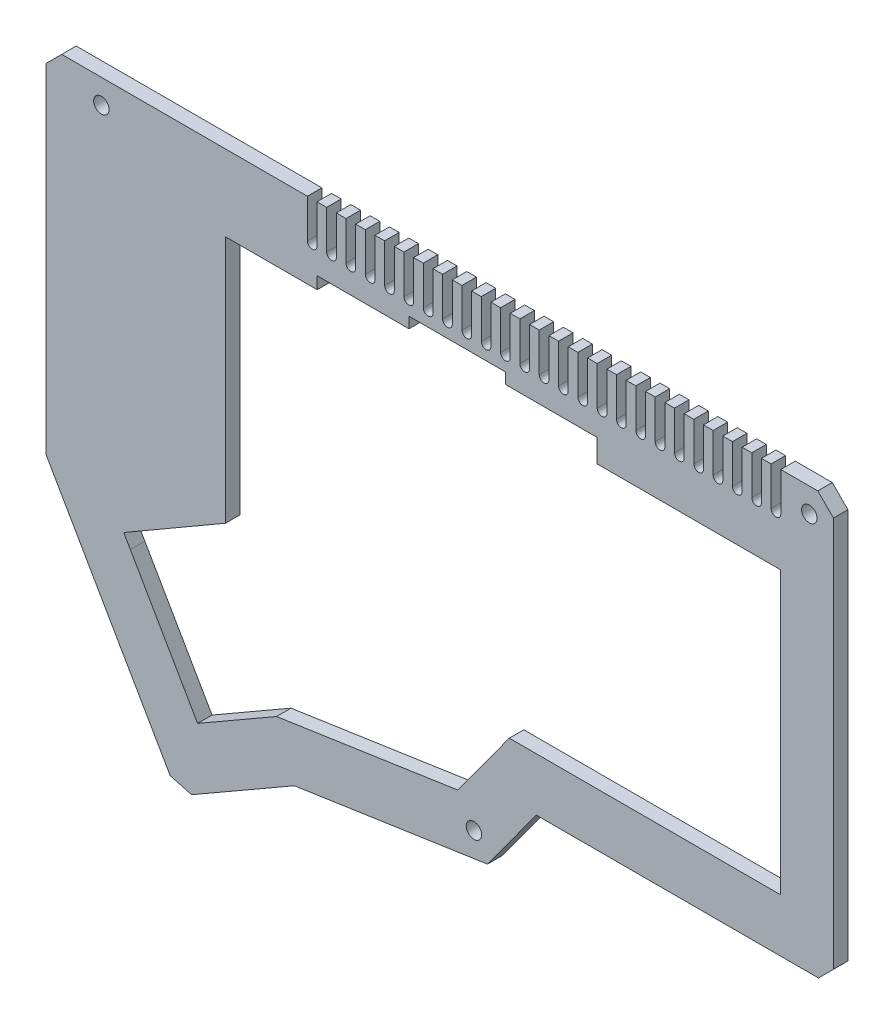
SolidWorks part; units mm, degrees
ref_plane "Plan de face" through (0, 0, 0) normal (0, 0, 1) x (1, 0, 0)
ref_plane "Plan de dessus" through (0, 0, 0) normal (0, 1, 0) x (1, 0, 0)
ref_plane "Plan de droite" through (0, 0, 0) normal (1, 0, 0) x (0, 0, -1)
sketch "Esquisse1" plane through (0, 0, 0) normal (0, 0, 1) x (1, 0, 0)
  line L0 (-117.3419, -15.4198) -> (-103.3409, -15.4198) construction
  line L1 (-103.3409, -15.4198) -> (-103.3409, -29.4208) construction
  line L2 (-103.3409, -29.4208) -> (-117.3419, -29.4208) construction
  line L3 (-117.3419, -29.4208) -> (-117.3419, -15.4198) construction
  line L4 (-98.3406, -27.0457) -> (-98.3406, -13.0447) construction
  line L5 (-98.3406, -13.0447) -> (-84.3396, -13.0447) construction
  line L6 (-84.3396, -13.0447) -> (-84.3396, -27.0457) construction
  line L7 (-84.3396, -27.0457) -> (-98.3406, -27.0457) construction
  line L8 (-79.3392, -24.6705) -> (-79.3392, -10.6695) construction
  line L9 (-79.3392, -10.6695) -> (-65.3382, -10.6695) construction
  line L10 (-65.3382, -10.6695) -> (-65.3382, -24.6705) construction
  line L11 (-65.3382, -24.6705) -> (-79.3392, -24.6705) construction
  line L12 (-60.3379, -27.0457) -> (-60.3379, -13.0447) construction
  line L13 (-60.3379, -13.0447) -> (-46.3369, -13.0447) construction
  line L14 (-46.3369, -13.0447) -> (-46.3369, -27.0457) construction
  line L15 (-46.3369, -27.0457) -> (-60.3379, -27.0457) construction
  line L16 (-41.3365, -31.796) -> (-41.3365, -17.795) construction
  line L17 (-41.3365, -17.795) -> (-27.3355, -17.795) construction
  line L18 (-27.3355, -17.795) -> (-27.3355, -31.796) construction
  line L19 (-27.3355, -31.796) -> (-41.3365, -31.796) construction
  line L20 (-22.3347, -31.796) -> (-22.3347, -17.795) construction
  line L21 (-22.3347, -17.795) -> (-8.3337, -17.795) construction
  line L22 (-8.3337, -17.795) -> (-8.3337, -31.796) construction
  line L23 (-8.3337, -31.796) -> (-22.3347, -31.796) construction
  line L24 (-117.3419, -34.4212) -> (-103.3409, -34.4212) construction
  line L25 (-103.3409, -34.4212) -> (-103.3409, -48.4222) construction
  line L26 (-103.3409, -48.4222) -> (-117.3419, -48.4222) construction
  line L27 (-117.3419, -48.4222) -> (-117.3419, -34.4212) construction
  line L28 (-98.3406, -32.046) -> (-84.3396, -32.046) construction
  line L29 (-84.3396, -32.046) -> (-84.3396, -46.047) construction
  line L30 (-84.3396, -46.047) -> (-98.3406, -46.047) construction
  line L31 (-98.3406, -46.047) -> (-98.3406, -32.046) construction
  line L32 (-79.3392, -29.6709) -> (-65.3382, -29.6709) construction
  line L33 (-65.3382, -29.6709) -> (-65.3382, -43.6718) construction
  line L34 (-65.3382, -43.6718) -> (-79.3392, -43.6718) construction
  line L35 (-79.3392, -43.6718) -> (-79.3392, -29.6709) construction
  line L36 (-60.3379, -32.046) -> (-46.3369, -32.046) construction
  line L37 (-46.3369, -32.046) -> (-46.3369, -46.047) construction
  line L38 (-46.3369, -46.047) -> (-60.3379, -46.047) construction
  line L39 (-60.3379, -46.047) -> (-60.3379, -32.046) construction
  line L40 (-41.3365, -36.7964) -> (-27.3355, -36.7964) construction
  line L41 (-27.3355, -36.7964) -> (-27.3355, -50.7973) construction
  line L42 (-27.3355, -50.7973) -> (-41.3365, -50.7973) construction
  line L43 (-41.3365, -50.7973) -> (-41.3365, -36.7964) construction
  line L44 (-22.3347, -36.7964) -> (-8.3337, -36.7964) construction
  line L45 (-8.3337, -36.7964) -> (-8.3337, -50.7973) construction
  line L46 (-8.3337, -50.7973) -> (-22.3347, -50.7973) construction
  line L47 (-22.3347, -50.7973) -> (-22.3347, -36.7964) construction
  line L48 (-22.3347, -55.7977) -> (-8.3337, -55.7977) construction
  line L49 (-8.3337, -55.7977) -> (-8.3337, -69.7987) construction
  line L50 (-8.3337, -69.7987) -> (-22.3347, -69.7987) construction
  line L51 (-22.3347, -69.7987) -> (-22.3347, -55.7977) construction
  line L52 (-41.3365, -55.7977) -> (-27.3355, -55.7977) construction
  line L53 (-27.3355, -55.7977) -> (-27.3355, -69.7987) construction
  line L54 (-27.3355, -69.7987) -> (-41.3365, -69.7987) construction
  line L55 (-41.3365, -69.7987) -> (-41.3365, -55.7977) construction
  line L56 (-60.3379, -51.0474) -> (-46.3369, -51.0474) construction
  line L57 (-46.3369, -51.0474) -> (-46.3369, -65.0484) construction
  line L58 (-46.3369, -65.0484) -> (-60.3379, -65.0484) construction
  line L59 (-60.3379, -65.0484) -> (-60.3379, -51.0474) construction
  line L60 (-79.3392, -48.6722) -> (-65.3382, -48.6722) construction
  line L61 (-65.3382, -48.6722) -> (-65.3382, -62.6732) construction
  line L62 (-65.3382, -62.6732) -> (-79.3392, -62.6732) construction
  line L63 (-79.3392, -62.6732) -> (-79.3392, -48.6722) construction
  line L64 (-98.3406, -51.0474) -> (-84.3396, -51.0474) construction
  line L65 (-84.3396, -51.0474) -> (-84.3396, -65.0484) construction
  line L66 (-84.3396, -65.0484) -> (-98.3406, -65.0484) construction
  line L67 (-98.3406, -65.0484) -> (-98.3406, -51.0474) construction
  line L68 (-117.3419, -53.4225) -> (-103.3409, -53.4225) construction
  line L69 (-103.3409, -53.4225) -> (-103.3409, -67.4235) construction
  line L70 (-103.3409, -67.4235) -> (-117.3419, -67.4235) construction
  line L71 (-117.3419, -67.4235) -> (-117.3419, -53.4225) construction
  line L72 (-88.8399, -70.6738) -> (-74.8389, -70.6738) construction
  line L73 (-74.8389, -70.6738) -> (-74.8389, -84.6747) construction
  line L74 (-74.8389, -84.6747) -> (-88.8399, -84.6747) construction
  line L75 (-88.8399, -84.6747) -> (-88.8399, -70.6738) construction
  line L76 (-111.4175, -75.4665) -> (-97.8899, -71.8565) construction
  line L77 (-97.8899, -71.8565) -> (-94.28, -85.3841) construction
  line L78 (-94.28, -85.3841) -> (-107.8075, -88.9941) construction
  line L79 (-107.8075, -88.9941) -> (-111.4175, -75.4665) construction
  line L80 (-134.6581, -81.5997) -> (-122.5281, -74.6075) construction
  line L81 (-122.5281, -74.6075) -> (-115.5359, -86.7375) construction
  line L82 (-115.5359, -86.7375) -> (-127.6659, -93.7297) construction
  line L83 (-127.6659, -93.7297) -> (-134.6581, -81.5997) construction
  line L86 (-6.475, -71.9336) -> (-62.0853, -71.9336) construction
  line L89 (-72.824, -86.6446) -> (-62.0853, -71.9336) construction
  line L96 (-109.7697, -91.4639) -> (-73.0906, -86.6918) construction
  line L97 (-124.664, -99.8297) -> (-110.3971, -91.5881) construction
  line L98 (-139.9408, -76.5013) -> (-126.7151, -99.4281) construction
  line L99 (-119.8527, -15.5421) -> (-139.6028, -15.5421) construction
  line L100 (-100.8528, -13.2921) -> (-118.8527, -13.2921) construction
  line L101 (-63.8455, -8.5421) -> (-80.8528, -8.5421) construction
  line L102 (-44.8455, -10.792) -> (-62.8485, -10.792) construction
  line L103 (-25.8456, -15.5421) -> (-43.8486, -15.5421) construction
  line L104 (-6.8456, -15.5421) -> (-23.8529, -15.5421) construction
  line L105 (-6.2741, -71.3672) -> (-6.2741, -16.1136) construction
  line L106 (-23.8529, -71.9423) -> (-6.8456, -71.9423) construction
  line L107 (-61.8455, -71.9423) -> (-25.8456, -71.9423) construction
  line L108 (-72.6738, -86.4911) -> (-62.1363, -72.0583) construction
  line L109 (-140.1743, -16.1136) -> (-140.1743, -75.5958) construction
  line L110 (-134.3462, 1.5705) -> (-134.3466, -55.7217) construction
  line L111 (-134.3466, -55.7217) -> (-160.479, -70.8411) construction
  line L112 (-160.479, -70.8411) -> (-133.7613, -117.344) construction
  line L113 (-126.937, -119.1852) -> (-105.0783, -106.604) construction
  line L114 (-105.0783, -106.604) -> (-64.4097, -100.5586) construction
  line L115 (-64.4097, -100.5586) -> (-54.4636, -86.9336) construction
  line L116 (3.6609, -86.9336) -> (-54.4636, -86.9336) construction
  line L117 (8.525, -82.0695) -> (8.525, 1.315) construction
  line L122 (3.525, 6.3153) -> (-96.3444, 6.3209) construction
  line L129 (8.525, -86.9336) -> (8.525, -0.6796) construction
  line L130 (-48.3431, 6.3182) -> (-96.3444, 6.3209) construction
  line L131 (-115.3458, 1.5705) -> (-134.3462, 1.5705) construction
  line L132 (-160.479, -3.4295) -> (-160.479, -70.8411) construction
  line L135 (-119.3466, -64.3728) -> (-135.695, -73.8315) construction
  line L136 (-140.0228, -76.3355) -> (-140.0228, -76.3321)
  line L138 (-160.479, -70.8411) -> (-131.2704, -121.6794) construction
  line L139 (-131.2704, -121.6794) -> (-105.0783, -106.604) construction
  line L140 (-133.7613, -117.344) -> (-126.937, -119.1852) construction
  line L142 (8.525, 1.315) -> (3.525, 6.3153) construction
  line L143 (8.525, -86.9336) -> (-54.4636, -86.9336) construction
  line L144 (8.525, -82.0695) -> (3.6609, -86.9336) construction
  line L148 (-103.3409, 6.3209) -> (-119.3463, 6.3209) construction
  line L149 (-119.3463, 6.3209) -> (-119.3463, 1.5705) construction
  line L150 (-140.0228, 1.5705) -> (-140.0228, 6.3209) construction
  line L151 (-140.0228, 6.3209) -> (-155.479, 6.3209) construction
  line L152 (-160.479, 1.3209) -> (-160.479, -3.4295) construction
  line L153 (-155.479, 6.3209) -> (-160.479, 1.3209) construction
  line L154 (8.525, -1.685) -> (-119.3463, -1.6779) construction
  line L155 (-146.0924, -79.8227) -> (-128.3223, -110.752) construction
  line L156 (-128.3223, -110.752) -> (-107.7547, -98.9139) construction
  line L157 (-140.0228, -78.3428) -> (-126.1111, -102.5565)
  line L158 (-126.1111, -102.5565) -> (-109.762, -93.1464)
  line L159 (-109.762, -93.1464) -> (-72.2631, -87.5722)
  line L160 (-72.2631, -87.5722) -> (-61.5772, -72.9336)
  line L161 (-5.475, -72.9336) -> (-61.5772, -72.9336)
  line L162 (-5.475, -72.9336) -> (-5.475, -14.6796)
  line L163 (-5.475, -14.6796) -> (-43.4777, -14.6796)
  line L164 (-43.4777, -14.6796) -> (-43.4777, -9.9293)
  line L165 (-43.4777, -9.9293) -> (-62.3431, -9.9293)
  line L166 (-62.3431, -9.9293) -> (-62.3431, -7.681)
  line L167 (-62.3431, -7.681) -> (-82.3444, -7.6799)
  line L168 (-82.3444, -7.6799) -> (-82.3444, -9.9293)
  line L169 (-82.3444, -9.9293) -> (-101.3458, -9.9293)
  line L170 (-101.3458, -9.9293) -> (-101.3458, -12.4295)
  line L171 (-101.3458, -12.4295) -> (-120.3463, -12.4295)
  line L172 (-120.3463, -12.4295) -> (-120.3466, -63.7961)
  line L173 (-120.3466, -63.7961) -> (-140.5236, -75.4699)
  line L174 (-107.7547, -98.9139) -> (-68.8973, -93.1378) construction
  line L175 (-68.8973, -93.1378) -> (-58.5285, -78.9336) construction
  line L176 (0.525, -78.9336) -> (-58.5285, -78.9336) construction
  line L177 (0.525, -78.9336) -> (0.525, -1.6845) construction
  line L178 (-62.3428, -1.681) -> (-82.3441, -1.6799) construction
  line L179 (0.525, -78.9336) -> (0.525, -14.6796) construction
  line L180 (-146.0228, -76.3355) -> (-146.0228, 1.5705) construction
  line L181 (-140.0228, -76.3355) -> (-140.0228, 1.5705) construction
  line L182 (-135.695, -73.8315) -> (-140.0228, -71.3355) construction
  line L185 (2.2768, 3.3209) -> (-116.3463, 3.3209)
  line L186 (-116.3463, 3.3209) -> (-116.3463, 1.5705) construction
  line L187 (-116.3463, 1.5705) -> (-116.3466, -66.103) construction
  line L188 (-116.3466, -66.103) -> (-135.6926, -77.2961) construction
  line L189 (-135.6926, -77.2961) -> (-143.0228, -73.0684) construction
  line L190 (-143.0228, -73.0684) -> (-143.0228, 1.5705) construction
  line L191 (-143.0228, 1.5705) -> (-143.0228, 3.3209) construction
  line L192 (-143.0228, 3.3209) -> (-154.2363, 3.3209)
  line L193 (-154.2363, 3.3209) -> (-157.479, 0.0782)
  line L194 (-157.479, 0.0782) -> (-157.479, -3.4295)
  line L195 (-157.479, -3.4295) -> (-157.479, -70.0407)
  line L196 (-157.479, -70.0407) -> (-131.7794, -114.7715)
  line L197 (-131.7794, -114.7715) -> (-127.3559, -115.9649)
  line L198 (-127.3559, -115.9649) -> (-106.082, -103.7202)
  line L199 (-106.082, -103.7202) -> (-66.0925, -97.7758)
  line L200 (-66.0925, -97.7758) -> (-55.988, -83.9336)
  line L201 (2.4183, -83.9336) -> (-55.988, -83.9336)
  line L202 (5.525, -80.8269) -> (2.4183, -83.9336)
  line L203 (5.525, -80.8269) -> (5.525, 0.0724)
  line L204 (5.525, 0.0724) -> (2.2768, 3.3209)
  line L205 (-143.0228, 3.3209) -> (-140.0228, 3.3209)
  line L206 (-140.8899, -76.8336) -> (-119.3466, -64.3728) construction
  line L207 (-140.0228, -71.3355) -> (-140.0228, 1.5705) construction
  line L208 (-119.3463, 3.3209) -> (-116.3463, 3.3209)
  line L209 (-140.8899, -76.8336) -> (-126.1111, -102.5565) construction
  line L210 (-119.3463, 1.5705) -> (-119.3466, -64.3728) construction
  line L211 (-101.3458, -12.4295) -> (-120.3463, -12.4295) construction
  line L212 (-119.3463, 3.3209) -> (-140.0228, 3.3209)
  line L213 (-120.3463, -12.4295) -> (-120.3466, -64.3728) construction
  line L217 (-6.475, -71.9336) -> (-6.475, -15.6796) construction
  line L220 (-6.475, -15.6796) -> (-44.4777, -15.6796) construction
  line L221 (-44.4777, -15.6796) -> (-44.4777, -10.9293) construction
  line L222 (-44.4777, -10.9293) -> (-63.3431, -10.9293) construction
  line L223 (-63.3431, -10.9293) -> (-63.3431, -8.681) construction
  line L224 (-63.3431, -8.681) -> (-81.3444, -8.68) construction
  line L225 (-81.3444, -8.68) -> (-81.3444, -10.9293) construction
  line L226 (-81.3444, -10.9293) -> (-100.3458, -10.9293) construction
  line L227 (-100.3458, -10.9293) -> (-100.3458, -13.4295) construction
  line L228 (-100.3458, -13.4295) -> (-119.3463, -13.4295) construction
  line L231 (-119.3463, -13.4295) -> (-119.3466, -64.3728) construction
  line L232 (-119.3466, -64.3728) -> (-140.0228, -76.3355) construction
  line L233 (-140.0228, -76.3355) -> (-125.7426, -101.1906) construction
  line L234 (-125.7426, -101.1906) -> (-110.0965, -92.1851) construction
  line L235 (-110.0965, -92.1851) -> (-72.824, -86.6446) construction
  line L236 (-140.0228, -71.3355) -> (-140.0228, -59.0058)
  line L237 (-119.8474, -63.5072) -> (-140.5236, -75.4699) construction
  line L238 (-140.5236, -75.4699) -> (-141.4072, -75.9811)
  line L239 (-141.4072, -75.9811) -> (-140.0228, -78.3428)
  line L240 (5.525, -5.3532) -> (-6.475, -5.3532) construction
  line L241 (-6.475, 3.3159) -> (-6.475, -6.6841) construction
  line L242 (5.525, 0.0724) -> (2.2822, 3.3154) construction
  line L322 (-103.3409, 3.3209) -> (-96.3445, 3.3209) construction
  line L323 (-103.3409, 3.3209) -> (-116.3463, 3.3209) construction
  line L328 (-48.3431, 4.0707) -> (-48.3431, 6.3182) construction
  line L329 (-29.4777, 4.0707) -> (-48.3431, 4.0707) construction
  line L330 (-29.4777, -0.6796) -> (-29.4777, 4.0707) construction
  line L331 (8.525, -0.6796) -> (-29.4777, -0.6796) construction
  line L332 (-115.3458, 4.0707) -> (-115.3458, 1.5705) construction
  line L333 (-96.3444, 4.0707) -> (-115.3458, 4.0707) construction
  line L334 (-96.3444, 6.3209) -> (-96.3444, 4.0707) construction
  line L343 (2.2822, 3.3154) -> (-96.3445, 3.3209) construction
  line L465 (-103.3409, 6.3209) -> (-96.3444, 6.3209) construction
  circle A2 centre (0.525, -1.6845) radius 1.6
  circle A3 centre (0.525, -1.6845) radius 3 construction
  circle A4 centre (-110.3971, -1.6784) radius 1.6 construction
  circle A5 centre (0.525, -78.9336) radius 1.6 construction
  circle A6 centre (-68.8973, -93.1378) radius 1.6
  circle A7 centre (-128.3223, -110.752) radius 1.6 construction
  circle A8 centre (-146.0924, -79.8227) radius 1.6 construction
  circle A9 centre (-146.0228, -1.6779) radius 1.6
  circle A10 centre (-110.3971, -1.6784) radius 3 construction
  circle A11 centre (-146.0228, -1.6779) radius 3 construction
  circle A12 centre (-146.0924, -79.8227) radius 3 construction
  circle A13 centre (-128.3223, -110.752) radius 3 construction
  circle A14 centre (-68.8973, -93.1378) radius 3 construction
  circle A15 centre (0.525, -78.9336) radius 3 construction
  point P138 (-160.479, 1.5705)
  point P139 (8.525, 6.315)
  point P150 (-160.479, 6.3209)
  dimension "D3" = 3.2
  dimension "D4" = 6
  dimension "D6" = 3.2
  dimension "D7" = 3.2
  dimension "D8" = 3.2
  dimension "D9" = 3.2
  dimension "D10" = 3.2
  dimension "D15" = 3.2
  dimension "D17" = 12
  dimension "D1" = 15
  dimension "D5" = 1
  dimension "D13" = 6
  dimension "D16" = 3
extrude "Boss.-Extru.1" add sketch "Esquisse1" along normal blind 3
sketch "Esquisse2" plane through (0, 0, 3) normal (0, 0, 1) x (1, 0, 0)
  line L0 (5.525, -5.6137) -> (-6.3866, -5.6137) construction
  line L1 (5.525, -80.8269) -> (5.525, 0.0724) construction
  line L2 (-6.3866, 3.3209) -> (-6.3866, -4.6791) construction
  line L3 (-154.2363, 3.3209) -> (2.2768, 3.3209) construction
  line L4 (-6.3866, 6.0542) -> (-6.3866, -4.6791) construction
  line L5 (-5.3866, 6.0542) -> (-5.3866, -4.6791)
  line L6 (-7.3866, 6.0542) -> (-7.3866, -4.6791)
  line L7 (-10.3866, 6.0542) -> (-10.3866, -4.6791) construction
  line L8 (-9.3866, 6.0542) -> (-9.3866, -4.6791)
  line L9 (-11.3866, 6.0542) -> (-11.3866, -4.6791)
  line L10 (-14.3866, 6.0542) -> (-14.3866, -4.6791) construction
  line L11 (-13.3866, 6.0542) -> (-13.3866, -4.6791)
  line L12 (-15.3866, 6.0542) -> (-15.3866, -4.6791)
  line L13 (-18.3866, 6.0542) -> (-18.3866, -4.6791) construction
  line L14 (-17.3866, 6.0542) -> (-17.3866, -4.6791)
  line L15 (-19.3866, 6.0542) -> (-19.3866, -4.6791)
  line L16 (-22.3866, 6.0542) -> (-22.3866, -4.6791) construction
  line L17 (-21.3866, 6.0542) -> (-21.3866, -4.6791)
  line L18 (-23.3866, 6.0542) -> (-23.3866, -4.6791)
  line L19 (-26.3866, 6.0542) -> (-26.3866, -4.6791) construction
  line L20 (-25.3866, 6.0542) -> (-25.3866, -4.6791)
  line L21 (-27.3866, 6.0542) -> (-27.3866, -4.6791)
  line L22 (-30.3866, 6.0542) -> (-30.3866, -4.6791) construction
  line L23 (-29.3866, 6.0542) -> (-29.3866, -4.6791)
  line L24 (-31.3866, 6.0542) -> (-31.3866, -4.6791)
  line L25 (-34.3866, 6.0542) -> (-34.3866, -4.6791) construction
  line L26 (-33.3866, 6.0542) -> (-33.3866, -4.6791)
  line L27 (-35.3866, 6.0542) -> (-35.3866, -4.6791)
  line L28 (-38.3866, 6.0542) -> (-38.3866, -4.6791) construction
  line L29 (-37.3866, 6.0542) -> (-37.3866, -4.6791)
  line L30 (-39.3866, 6.0542) -> (-39.3866, -4.6791)
  line L31 (-42.3866, 6.0542) -> (-42.3866, -4.6791) construction
  line L32 (-41.3866, 6.0542) -> (-41.3866, -4.6791)
  line L33 (-43.3866, 6.0542) -> (-43.3866, -4.6791)
  line L34 (-46.3866, 6.0542) -> (-46.3866, -4.6791) construction
  line L35 (-45.3866, 6.0542) -> (-45.3866, -4.6791)
  line L36 (-47.3866, 6.0542) -> (-47.3866, -4.6791)
  line L37 (-50.3866, 6.0542) -> (-50.3866, -4.6791) construction
  line L38 (-49.3866, 6.0542) -> (-49.3866, -4.6791)
  line L39 (-51.3866, 6.0542) -> (-51.3866, -4.6791)
  line L40 (-54.3866, 6.0542) -> (-54.3866, -4.6791) construction
  line L41 (-53.3866, 6.0542) -> (-53.3866, -4.6791)
  line L42 (-55.3866, 6.0542) -> (-55.3866, -4.6791)
  line L43 (-58.3866, 6.0542) -> (-58.3866, -4.6791) construction
  line L44 (-57.3866, 6.0542) -> (-57.3866, -4.6791)
  line L45 (-59.3866, 6.0542) -> (-59.3866, -4.6791)
  line L46 (-62.3866, 6.0542) -> (-62.3866, -4.6791) construction
  line L47 (-61.3866, 6.0542) -> (-61.3866, -4.6791)
  line L48 (-63.3866, 6.0542) -> (-63.3866, -4.6791)
  line L49 (-66.3866, 6.0542) -> (-66.3866, -4.6791) construction
  line L50 (-65.3866, 6.0542) -> (-65.3866, -4.6791)
  line L51 (-67.3866, 6.0542) -> (-67.3866, -4.6791)
  line L52 (-70.3866, 6.0542) -> (-70.3866, -4.6791) construction
  line L53 (-69.3866, 6.0542) -> (-69.3866, -4.6791)
  line L54 (-71.3866, 6.0542) -> (-71.3866, -4.6791)
  line L55 (-74.3866, 6.0542) -> (-74.3866, -4.6791) construction
  line L56 (-73.3866, 6.0542) -> (-73.3866, -4.6791)
  line L57 (-75.3866, 6.0542) -> (-75.3866, -4.6791)
  line L58 (-78.3866, 6.0542) -> (-78.3866, -4.6791) construction
  line L59 (-77.3866, 6.0542) -> (-77.3866, -4.6791)
  line L60 (-79.3866, 6.0542) -> (-79.3866, -4.6791)
  line L61 (-82.3866, 6.0542) -> (-82.3866, -4.6791) construction
  line L62 (-81.3866, 6.0542) -> (-81.3866, -4.6791)
  line L63 (-83.3866, 6.0542) -> (-83.3866, -4.6791)
  line L64 (-86.3866, 6.0542) -> (-86.3866, -4.6791) construction
  line L65 (-85.3866, 6.0542) -> (-85.3866, -4.6791)
  line L66 (-87.3866, 6.0542) -> (-87.3866, -4.6791)
  line L67 (-90.3866, 6.0542) -> (-90.3866, -4.6791) construction
  line L68 (-89.3866, 6.0542) -> (-89.3866, -4.6791)
  line L69 (-91.3866, 6.0542) -> (-91.3866, -4.6791)
  line L70 (-94.3866, 6.0542) -> (-94.3866, -4.6791) construction
  line L71 (-93.3866, 6.0542) -> (-93.3866, -4.6791)
  line L72 (-95.3866, 6.0542) -> (-95.3866, -4.6791)
  line L73 (-98.3866, 6.0542) -> (-98.3866, -4.6791) construction
  line L74 (-97.3866, 6.0542) -> (-97.3866, -4.6791)
  line L75 (-99.3866, 6.0542) -> (-99.3866, -4.6791)
  line L76 (-102.3866, 6.0542) -> (-102.3866, -4.6791) construction
  line L77 (-101.3866, 6.0542) -> (-101.3866, -4.6791)
  line L78 (-103.3866, 6.0542) -> (-103.3866, -4.6791)
  arc A0 (-5.3866, 6.0542) -> (-7.3866, 6.0542) centre (-6.3866, 6.0542) ccw
  arc A1 (-7.3866, -4.6791) -> (-5.3866, -4.6791) centre (-6.3866, -4.6791) ccw
  arc A2 (-9.3866, 6.0542) -> (-11.3866, 6.0542) centre (-10.3866, 6.0542) ccw
  arc A3 (-11.3866, -4.6791) -> (-9.3866, -4.6791) centre (-10.3866, -4.6791) ccw
  arc A4 (-13.3866, 6.0542) -> (-15.3866, 6.0542) centre (-14.3866, 6.0542) ccw
  arc A5 (-15.3866, -4.6791) -> (-13.3866, -4.6791) centre (-14.3866, -4.6791) ccw
  arc A6 (-17.3866, 6.0542) -> (-19.3866, 6.0542) centre (-18.3866, 6.0542) ccw
  arc A7 (-19.3866, -4.6791) -> (-17.3866, -4.6791) centre (-18.3866, -4.6791) ccw
  arc A8 (-21.3866, 6.0542) -> (-23.3866, 6.0542) centre (-22.3866, 6.0542) ccw
  arc A9 (-23.3866, -4.6791) -> (-21.3866, -4.6791) centre (-22.3866, -4.6791) ccw
  arc A10 (-25.3866, 6.0542) -> (-27.3866, 6.0542) centre (-26.3866, 6.0542) ccw
  arc A11 (-27.3866, -4.6791) -> (-25.3866, -4.6791) centre (-26.3866, -4.6791) ccw
  arc A12 (-29.3866, 6.0542) -> (-31.3866, 6.0542) centre (-30.3866, 6.0542) ccw
  arc A13 (-31.3866, -4.6791) -> (-29.3866, -4.6791) centre (-30.3866, -4.6791) ccw
  arc A14 (-33.3866, 6.0542) -> (-35.3866, 6.0542) centre (-34.3866, 6.0542) ccw
  arc A15 (-35.3866, -4.6791) -> (-33.3866, -4.6791) centre (-34.3866, -4.6791) ccw
  arc A16 (-37.3866, 6.0542) -> (-39.3866, 6.0542) centre (-38.3866, 6.0542) ccw
  arc A17 (-39.3866, -4.6791) -> (-37.3866, -4.6791) centre (-38.3866, -4.6791) ccw
  arc A18 (-41.3866, 6.0542) -> (-43.3866, 6.0542) centre (-42.3866, 6.0542) ccw
  arc A19 (-43.3866, -4.6791) -> (-41.3866, -4.6791) centre (-42.3866, -4.6791) ccw
  arc A20 (-45.3866, 6.0542) -> (-47.3866, 6.0542) centre (-46.3866, 6.0542) ccw
  arc A21 (-47.3866, -4.6791) -> (-45.3866, -4.6791) centre (-46.3866, -4.6791) ccw
  arc A22 (-49.3866, 6.0542) -> (-51.3866, 6.0542) centre (-50.3866, 6.0542) ccw
  arc A23 (-51.3866, -4.6791) -> (-49.3866, -4.6791) centre (-50.3866, -4.6791) ccw
  arc A24 (-53.3866, 6.0542) -> (-55.3866, 6.0542) centre (-54.3866, 6.0542) ccw
  arc A25 (-55.3866, -4.6791) -> (-53.3866, -4.6791) centre (-54.3866, -4.6791) ccw
  arc A26 (-57.3866, 6.0542) -> (-59.3866, 6.0542) centre (-58.3866, 6.0542) ccw
  arc A27 (-59.3866, -4.6791) -> (-57.3866, -4.6791) centre (-58.3866, -4.6791) ccw
  arc A28 (-61.3866, 6.0542) -> (-63.3866, 6.0542) centre (-62.3866, 6.0542) ccw
  arc A29 (-63.3866, -4.6791) -> (-61.3866, -4.6791) centre (-62.3866, -4.6791) ccw
  arc A30 (-65.3866, 6.0542) -> (-67.3866, 6.0542) centre (-66.3866, 6.0542) ccw
  arc A31 (-67.3866, -4.6791) -> (-65.3866, -4.6791) centre (-66.3866, -4.6791) ccw
  arc A32 (-69.3866, 6.0542) -> (-71.3866, 6.0542) centre (-70.3866, 6.0542) ccw
  arc A33 (-71.3866, -4.6791) -> (-69.3866, -4.6791) centre (-70.3866, -4.6791) ccw
  arc A34 (-73.3866, 6.0542) -> (-75.3866, 6.0542) centre (-74.3866, 6.0542) ccw
  arc A35 (-75.3866, -4.6791) -> (-73.3866, -4.6791) centre (-74.3866, -4.6791) ccw
  arc A36 (-77.3866, 6.0542) -> (-79.3866, 6.0542) centre (-78.3866, 6.0542) ccw
  arc A37 (-79.3866, -4.6791) -> (-77.3866, -4.6791) centre (-78.3866, -4.6791) ccw
  arc A38 (-81.3866, 6.0542) -> (-83.3866, 6.0542) centre (-82.3866, 6.0542) ccw
  arc A39 (-83.3866, -4.6791) -> (-81.3866, -4.6791) centre (-82.3866, -4.6791) ccw
  arc A40 (-85.3866, 6.0542) -> (-87.3866, 6.0542) centre (-86.3866, 6.0542) ccw
  arc A41 (-87.3866, -4.6791) -> (-85.3866, -4.6791) centre (-86.3866, -4.6791) ccw
  arc A42 (-89.3866, 6.0542) -> (-91.3866, 6.0542) centre (-90.3866, 6.0542) ccw
  arc A43 (-91.3866, -4.6791) -> (-89.3866, -4.6791) centre (-90.3866, -4.6791) ccw
  arc A44 (-93.3866, 6.0542) -> (-95.3866, 6.0542) centre (-94.3866, 6.0542) ccw
  arc A45 (-95.3866, -4.6791) -> (-93.3866, -4.6791) centre (-94.3866, -4.6791) ccw
  arc A46 (-97.3866, 6.0542) -> (-99.3866, 6.0542) centre (-98.3866, 6.0542) ccw
  arc A47 (-99.3866, -4.6791) -> (-97.3866, -4.6791) centre (-98.3866, -4.6791) ccw
  arc A48 (-101.3866, 6.0542) -> (-103.3866, 6.0542) centre (-102.3866, 6.0542) ccw
  arc A49 (-103.3866, -4.6791) -> (-101.3866, -4.6791) centre (-102.3866, -4.6791) ccw
  point P9 (-6.3866, 0.6875)
  point P17 (-10.3866, 0.6875)
  point P24 (-14.3866, 0.6875)
  point P31 (-18.3866, 0.6875)
  point P38 (-22.3866, 0.6875)
  point P45 (-26.3866, 0.6875)
  point P52 (-30.3866, 0.6875)
  point P59 (-34.3866, 0.6875)
  point P66 (-38.3866, 0.6875)
  point P73 (-42.3866, 0.6875)
  point P80 (-46.3866, 0.6875)
  point P87 (-50.3866, 0.6875)
  point P94 (-54.3866, 0.6875)
  point P101 (-58.3866, 0.6875)
  point P108 (-62.3866, 0.6875)
  point P115 (-66.3866, 0.6875)
  point P122 (-70.3866, 0.6875)
  point P129 (-74.3866, 0.6875)
  point P136 (-78.3866, 0.6875)
  point P143 (-82.3866, 0.6875)
  point P150 (-86.3866, 0.6875)
  point P157 (-90.3866, 0.6875)
  point P164 (-94.3866, 0.6875)
  point P171 (-98.3866, 0.6875)
  point P178 (-102.3866, 0.6875)
  dimension "D1" = 25
extrude "Enlèv. mat.-Extru.1" cut sketch "Esquisse2" against normal blind 10
sketch "Esquisse3" plane through (0, 0, 3) normal (0, 0, 1) x (1, 0, 0)
  line L19 (-141.4072, -75.9811) -> (-140.0228, -78.3428)
  line L20 (-120.3466, -63.7961) -> (-141.4072, -75.9811)
  line L21 (-120.3463, -12.4295) -> (-120.3466, -63.7961)
  line L22 (-101.3458, -12.4295) -> (-120.3463, -12.4295)
  line L23 (-101.3458, -9.9293) -> (-101.3458, -12.4295)
  line L24 (-82.3444, -9.9293) -> (-101.3458, -9.9293)
  line L25 (-82.3444, -7.6799) -> (-82.3444, -9.9293)
  line L26 (-62.3431, -7.681) -> (-82.3444, -7.6799)
  line L27 (-62.3431, -9.9293) -> (-62.3431, -7.681)
  line L28 (-43.4777, -9.9293) -> (-62.3431, -9.9293)
  line L29 (-43.4777, -14.6796) -> (-43.4777, -9.9293)
  line L30 (-5.475, -14.6796) -> (-43.4777, -14.6796)
  line L31 (-5.475, -72.9336) -> (-5.475, -14.6796)
  line L32 (-61.5772, -72.9336) -> (-5.475, -72.9336)
  line L33 (-72.2631, -87.5722) -> (-61.5772, -72.9336)
  line L34 (-109.762, -93.1464) -> (-72.2631, -87.5722)
  line L35 (-126.1111, -102.5565) -> (-109.762, -93.1464)
  line L36 (-140.0228, -78.3428) -> (-126.1111, -102.5565)
  line L37 (-141.4072, -75.9811) -> (-140.0228, -78.3428)
  line L38 (-120.3466, -63.7961) -> (-141.4072, -75.9811)
  line L39 (-120.3463, -12.4295) -> (-120.3466, -63.7961)
  line L40 (-101.3458, -12.4295) -> (-120.3463, -12.4295)
  line L41 (-101.3458, -9.9293) -> (-101.3458, -12.4295)
  line L42 (-82.3444, -9.9293) -> (-101.3458, -9.9293)
  line L43 (-82.3444, -7.6799) -> (-82.3444, -9.9293)
  line L44 (-62.3431, -7.681) -> (-82.3444, -7.6799)
  line L45 (-62.3431, -9.9293) -> (-62.3431, -7.681)
  line L46 (-43.4777, -9.9293) -> (-62.3431, -9.9293)
  line L47 (-43.4777, -14.6796) -> (-43.4777, -9.9293)
  line L48 (-5.475, -14.6796) -> (-43.4777, -14.6796)
  line L49 (-5.475, -72.9336) -> (-5.475, -14.6796)
  line L50 (-61.5772, -72.9336) -> (-5.475, -72.9336)
  line L51 (-72.2631, -87.5722) -> (-61.5772, -72.9336)
  line L52 (-109.762, -93.1464) -> (-72.2631, -87.5722)
  line L53 (-126.1111, -102.5565) -> (-109.762, -93.1464)
  line L54 (-140.0228, -78.3428) -> (-126.1111, -102.5565)
  line L87 (-5.3866, 3.3209) -> (-5.3866, -4.6791)
  line L88 (-7.3866, -4.6791) -> (-7.3866, 3.3209)
  line L89 (-7.3866, 3.3209) -> (-9.3866, 3.3209)
  line L90 (-9.3866, 3.3209) -> (-9.3866, -4.6791)
  line L91 (-11.3866, -4.6791) -> (-11.3866, 3.3209)
  line L92 (-11.3866, 3.3209) -> (-13.3866, 3.3209)
  line L93 (-13.3866, 3.3209) -> (-13.3866, -4.6791)
  line L94 (-15.3866, -4.6791) -> (-15.3866, 3.3209)
  line L95 (-15.3866, 3.3209) -> (-17.3866, 3.3209)
  line L96 (-17.3866, 3.3209) -> (-17.3866, -4.6791)
  line L97 (-19.3866, -4.6791) -> (-19.3866, 3.3209)
  line L98 (-19.3866, 3.3209) -> (-21.3866, 3.3209)
  line L99 (-21.3866, 3.3209) -> (-21.3866, -4.6791)
  line L100 (-23.3866, -4.6791) -> (-23.3866, 3.3209)
  line L101 (-23.3866, 3.3209) -> (-25.3866, 3.3209)
  line L102 (-25.3866, 3.3209) -> (-25.3866, -4.6791)
  line L103 (-27.3866, -4.6791) -> (-27.3866, 3.3209)
  line L104 (-27.3866, 3.3209) -> (-29.3866, 3.3209)
  line L105 (-29.3866, 3.3209) -> (-29.3866, -4.6791)
  line L106 (-31.3866, -4.6791) -> (-31.3866, 3.3209)
  line L107 (-31.3866, 3.3209) -> (-33.3866, 3.3209)
  line L108 (-33.3866, 3.3209) -> (-33.3866, -4.6791)
  line L109 (-35.3866, -4.6791) -> (-35.3866, 3.3209)
  line L110 (-35.3866, 3.3209) -> (-37.3866, 3.3209)
  line L111 (-37.3866, 3.3209) -> (-37.3866, -4.6791)
  line L112 (-39.3866, -4.6791) -> (-39.3866, 3.3209)
  line L113 (-39.3866, 3.3209) -> (-41.3866, 3.3209)
  line L114 (-41.3866, 3.3209) -> (-41.3866, -4.6791)
  line L115 (-43.3866, -4.6791) -> (-43.3866, 3.3209)
  line L116 (-43.3866, 3.3209) -> (-45.3866, 3.3209)
  line L117 (-45.3866, 3.3209) -> (-45.3866, -4.6791)
  line L118 (-47.3866, -4.6791) -> (-47.3866, 3.3209)
  line L119 (-47.3866, 3.3209) -> (-49.3866, 3.3209)
  line L120 (-49.3866, 3.3209) -> (-49.3866, -4.6791)
  line L121 (-51.3866, -4.6791) -> (-51.3866, 3.3209)
  line L122 (-51.3866, 3.3209) -> (-53.3866, 3.3209)
  line L123 (-53.3866, 3.3209) -> (-53.3866, -4.6791)
  line L124 (-55.3866, -4.6791) -> (-55.3866, 3.3209)
  line L125 (-55.3866, 3.3209) -> (-57.3866, 3.3209)
  line L126 (-57.3866, 3.3209) -> (-57.3866, -4.6791)
  line L127 (-59.3866, -4.6791) -> (-59.3866, 3.3209)
  line L128 (-59.3866, 3.3209) -> (-61.3866, 3.3209)
  line L129 (-61.3866, 3.3209) -> (-61.3866, -4.6791)
  line L130 (-63.3866, -4.6791) -> (-63.3866, 3.3209)
  line L131 (-63.3866, 3.3209) -> (-65.3866, 3.3209)
  line L132 (-65.3866, 3.3209) -> (-65.3866, -4.6791)
  line L133 (-67.3866, -4.6791) -> (-67.3866, 3.3209)
  line L134 (-67.3866, 3.3209) -> (-69.3866, 3.3209)
  line L135 (-69.3866, 3.3209) -> (-69.3866, -4.6791)
  line L136 (-71.3866, -4.6791) -> (-71.3866, 3.3209)
  line L137 (-71.3866, 3.3209) -> (-73.3866, 3.3209)
  line L138 (-73.3866, 3.3209) -> (-73.3866, -4.6791)
  line L139 (-75.3866, -4.6791) -> (-75.3866, 3.3209)
  line L140 (-75.3866, 3.3209) -> (-77.3866, 3.3209)
  line L141 (-77.3866, 3.3209) -> (-77.3866, -4.6791)
  line L142 (-79.3866, -4.6791) -> (-79.3866, 3.3209)
  line L143 (-79.3866, 3.3209) -> (-81.3866, 3.3209)
  line L144 (-81.3866, 3.3209) -> (-81.3866, -4.6791)
  line L145 (-83.3866, -4.6791) -> (-83.3866, 3.3209)
  line L146 (-83.3866, 3.3209) -> (-85.3866, 3.3209)
  line L147 (-85.3866, 3.3209) -> (-85.3866, -4.6791)
  line L148 (-87.3866, -4.6791) -> (-87.3866, 3.3209)
  line L149 (-87.3866, 3.3209) -> (-89.3866, 3.3209)
  line L150 (-89.3866, 3.3209) -> (-89.3866, -4.6791)
  line L151 (-91.3866, -4.6791) -> (-91.3866, 3.3209)
  line L152 (-91.3866, 3.3209) -> (-93.3866, 3.3209)
  line L153 (-93.3866, 3.3209) -> (-93.3866, -4.6791)
  line L154 (-95.3866, -4.6791) -> (-95.3866, 3.3209)
  line L155 (-95.3866, 3.3209) -> (-97.3866, 3.3209)
  line L156 (-97.3866, 3.3209) -> (-97.3866, -4.6791)
  line L157 (-99.3866, -4.6791) -> (-99.3866, 3.3209)
  line L158 (-99.3866, 3.3209) -> (-101.3866, 3.3209)
  line L159 (-101.3866, 3.3209) -> (-101.3866, -4.6791)
  line L160 (-103.3866, -4.6791) -> (-103.3866, 3.3209)
  line L161 (-103.3866, 3.3209) -> (-154.2363, 3.3209)
  line L162 (-154.2363, 3.3209) -> (-157.479, 0.0782)
  line L163 (-157.479, 0.0782) -> (-157.479, -70.0407)
  line L164 (-157.479, -70.0407) -> (-131.7794, -114.7715)
  line L165 (-131.7794, -114.7715) -> (-127.3559, -115.9649)
  line L166 (-127.3559, -115.9649) -> (-106.082, -103.7202)
  line L167 (-106.082, -103.7202) -> (-66.0925, -97.7758)
  line L168 (-66.0925, -97.7758) -> (-55.988, -83.9336)
  line L169 (-55.988, -83.9336) -> (2.4183, -83.9336)
  line L170 (2.4183, -83.9336) -> (5.525, -80.8269)
  line L171 (5.525, -80.8269) -> (5.525, 0.0724)
  line L172 (5.525, 0.0724) -> (2.2768, 3.3209)
  line L173 (2.2768, 3.3209) -> (-5.3866, 3.3209)
  line L174 (-5.3866, 3.3209) -> (-5.3866, -4.6791)
  line L175 (-7.3866, -4.6791) -> (-7.3866, 3.3209)
  line L176 (-7.3866, 3.3209) -> (-9.3866, 3.3209)
  line L177 (-9.3866, 3.3209) -> (-9.3866, -4.6791)
  line L178 (-11.3866, -4.6791) -> (-11.3866, 3.3209)
  line L179 (-11.3866, 3.3209) -> (-13.3866, 3.3209)
  line L180 (-13.3866, 3.3209) -> (-13.3866, -4.6791)
  line L181 (-15.3866, -4.6791) -> (-15.3866, 3.3209)
  line L182 (-15.3866, 3.3209) -> (-17.3866, 3.3209)
  line L183 (-17.3866, 3.3209) -> (-17.3866, -4.6791)
  line L184 (-19.3866, -4.6791) -> (-19.3866, 3.3209)
  line L185 (-19.3866, 3.3209) -> (-21.3866, 3.3209)
  line L186 (-21.3866, 3.3209) -> (-21.3866, -4.6791)
  line L187 (-23.3866, -4.6791) -> (-23.3866, 3.3209)
  line L188 (-23.3866, 3.3209) -> (-25.3866, 3.3209)
  line L189 (-25.3866, 3.3209) -> (-25.3866, -4.6791)
  line L190 (-27.3866, -4.6791) -> (-27.3866, 3.3209)
  line L191 (-27.3866, 3.3209) -> (-29.3866, 3.3209)
  line L192 (-29.3866, 3.3209) -> (-29.3866, -4.6791)
  line L193 (-31.3866, -4.6791) -> (-31.3866, 3.3209)
  line L194 (-31.3866, 3.3209) -> (-33.3866, 3.3209)
  line L195 (-33.3866, 3.3209) -> (-33.3866, -4.6791)
  line L196 (-35.3866, -4.6791) -> (-35.3866, 3.3209)
  line L197 (-35.3866, 3.3209) -> (-37.3866, 3.3209)
  line L198 (-37.3866, 3.3209) -> (-37.3866, -4.6791)
  line L199 (-39.3866, -4.6791) -> (-39.3866, 3.3209)
  line L200 (-39.3866, 3.3209) -> (-41.3866, 3.3209)
  line L201 (-41.3866, 3.3209) -> (-41.3866, -4.6791)
  line L202 (-43.3866, -4.6791) -> (-43.3866, 3.3209)
  line L203 (-43.3866, 3.3209) -> (-45.3866, 3.3209)
  line L204 (-45.3866, 3.3209) -> (-45.3866, -4.6791)
  line L205 (-47.3866, -4.6791) -> (-47.3866, 3.3209)
  line L206 (-47.3866, 3.3209) -> (-49.3866, 3.3209)
  line L207 (-49.3866, 3.3209) -> (-49.3866, -4.6791)
  line L208 (-51.3866, -4.6791) -> (-51.3866, 3.3209)
  line L209 (-51.3866, 3.3209) -> (-53.3866, 3.3209)
  line L210 (-53.3866, 3.3209) -> (-53.3866, -4.6791)
  line L211 (-55.3866, -4.6791) -> (-55.3866, 3.3209)
  line L212 (-55.3866, 3.3209) -> (-57.3866, 3.3209)
  line L213 (-57.3866, 3.3209) -> (-57.3866, -4.6791)
  line L214 (-59.3866, -4.6791) -> (-59.3866, 3.3209)
  line L215 (-59.3866, 3.3209) -> (-61.3866, 3.3209)
  line L216 (-61.3866, 3.3209) -> (-61.3866, -4.6791)
  line L217 (-63.3866, -4.6791) -> (-63.3866, 3.3209)
  line L218 (-63.3866, 3.3209) -> (-65.3866, 3.3209)
  line L219 (-65.3866, 3.3209) -> (-65.3866, -4.6791)
  line L220 (-67.3866, -4.6791) -> (-67.3866, 3.3209)
  line L221 (-67.3866, 3.3209) -> (-69.3866, 3.3209)
  line L222 (-69.3866, 3.3209) -> (-69.3866, -4.6791)
  line L223 (-71.3866, -4.6791) -> (-71.3866, 3.3209)
  line L224 (-71.3866, 3.3209) -> (-73.3866, 3.3209)
  line L225 (-73.3866, 3.3209) -> (-73.3866, -4.6791)
  line L226 (-75.3866, -4.6791) -> (-75.3866, 3.3209)
  line L227 (-75.3866, 3.3209) -> (-77.3866, 3.3209)
  line L228 (-77.3866, 3.3209) -> (-77.3866, -4.6791)
  line L229 (-79.3866, -4.6791) -> (-79.3866, 3.3209)
  line L230 (-79.3866, 3.3209) -> (-81.3866, 3.3209)
  line L231 (-81.3866, 3.3209) -> (-81.3866, -4.6791)
  line L232 (-83.3866, -4.6791) -> (-83.3866, 3.3209)
  line L233 (-83.3866, 3.3209) -> (-85.3866, 3.3209)
  line L234 (-85.3866, 3.3209) -> (-85.3866, -4.6791)
  line L235 (-87.3866, -4.6791) -> (-87.3866, 3.3209)
  line L236 (-87.3866, 3.3209) -> (-89.3866, 3.3209)
  line L237 (-89.3866, 3.3209) -> (-89.3866, -4.6791)
  line L238 (-91.3866, -4.6791) -> (-91.3866, 3.3209)
  line L239 (-91.3866, 3.3209) -> (-93.3866, 3.3209)
  line L240 (-93.3866, 3.3209) -> (-93.3866, -4.6791)
  line L241 (-95.3866, -4.6791) -> (-95.3866, 3.3209)
  line L242 (-95.3866, 3.3209) -> (-97.3866, 3.3209)
  line L243 (-97.3866, 3.3209) -> (-97.3866, -4.6791)
  line L244 (-99.3866, -4.6791) -> (-99.3866, 3.3209)
  line L245 (-99.3866, 3.3209) -> (-101.3866, 3.3209)
  line L246 (-101.3866, 3.3209) -> (-101.3866, -4.6791)
  line L247 (-103.3866, -4.6791) -> (-103.3866, 3.3209)
  line L248 (-103.3866, 3.3209) -> (-154.2363, 3.3209)
  line L249 (-154.2363, 3.3209) -> (-157.479, 0.0782)
  line L250 (-157.479, 0.0782) -> (-157.479, -70.0407)
  line L251 (-157.479, -70.0407) -> (-131.7794, -114.7715)
  line L252 (-131.7794, -114.7715) -> (-127.3559, -115.9649)
  line L253 (-127.3559, -115.9649) -> (-106.082, -103.7202)
  line L254 (-106.082, -103.7202) -> (-66.0925, -97.7758)
  line L255 (-66.0925, -97.7758) -> (-55.988, -83.9336)
  line L256 (-55.988, -83.9336) -> (2.4183, -83.9336)
  line L257 (2.4183, -83.9336) -> (5.525, -80.8269)
  line L258 (5.525, -80.8269) -> (5.525, 0.0724)
  line L259 (5.525, 0.0724) -> (2.2768, 3.3209)
  line L260 (2.2768, 3.3209) -> (-5.3866, 3.3209)
  circle A0 centre (-68.8973, -93.1378) radius 1.6 construction
  circle A1 centre (0.525, -1.6845) radius 1.6 construction
  circle A2 centre (-146.0228, -1.6779) radius 1.6 construction
  circle A3 centre (-68.8973, -93.1378) radius 1.6
  circle A4 centre (0.525, -1.6845) radius 1.6
  circle A5 centre (-146.0228, -1.6779) radius 1.6
  arc A25 (-7.3866, -4.6791) -> (-5.3866, -4.6791) centre (-6.3866, -4.6791) ccw
  arc A26 (-11.3866, -4.6791) -> (-9.3866, -4.6791) centre (-10.3866, -4.6791) ccw
  arc A27 (-15.3866, -4.6791) -> (-13.3866, -4.6791) centre (-14.3866, -4.6791) ccw
  arc A28 (-19.3866, -4.6791) -> (-17.3866, -4.6791) centre (-18.3866, -4.6791) ccw
  arc A29 (-23.3866, -4.6791) -> (-21.3866, -4.6791) centre (-22.3866, -4.6791) ccw
  arc A30 (-27.3866, -4.6791) -> (-25.3866, -4.6791) centre (-26.3866, -4.6791) ccw
  arc A31 (-31.3866, -4.6791) -> (-29.3866, -4.6791) centre (-30.3866, -4.6791) ccw
  arc A32 (-35.3866, -4.6791) -> (-33.3866, -4.6791) centre (-34.3866, -4.6791) ccw
  arc A33 (-39.3866, -4.6791) -> (-37.3866, -4.6791) centre (-38.3866, -4.6791) ccw
  arc A34 (-43.3866, -4.6791) -> (-41.3866, -4.6791) centre (-42.3866, -4.6791) ccw
  arc A35 (-47.3866, -4.6791) -> (-45.3866, -4.6791) centre (-46.3866, -4.6791) ccw
  arc A36 (-51.3866, -4.6791) -> (-49.3866, -4.6791) centre (-50.3866, -4.6791) ccw
  arc A37 (-55.3866, -4.6791) -> (-53.3866, -4.6791) centre (-54.3866, -4.6791) ccw
  arc A38 (-59.3866, -4.6791) -> (-57.3866, -4.6791) centre (-58.3866, -4.6791) ccw
  arc A39 (-63.3866, -4.6791) -> (-61.3866, -4.6791) centre (-62.3866, -4.6791) ccw
  arc A40 (-67.3866, -4.6791) -> (-65.3866, -4.6791) centre (-66.3866, -4.6791) ccw
  arc A41 (-71.3866, -4.6791) -> (-69.3866, -4.6791) centre (-70.3866, -4.6791) ccw
  arc A42 (-75.3866, -4.6791) -> (-73.3866, -4.6791) centre (-74.3866, -4.6791) ccw
  arc A43 (-79.3866, -4.6791) -> (-77.3866, -4.6791) centre (-78.3866, -4.6791) ccw
  arc A44 (-83.3866, -4.6791) -> (-81.3866, -4.6791) centre (-82.3866, -4.6791) ccw
  arc A45 (-87.3866, -4.6791) -> (-85.3866, -4.6791) centre (-86.3866, -4.6791) ccw
  arc A46 (-91.3866, -4.6791) -> (-89.3866, -4.6791) centre (-90.3866, -4.6791) ccw
  arc A47 (-95.3866, -4.6791) -> (-93.3866, -4.6791) centre (-94.3866, -4.6791) ccw
  arc A48 (-99.3866, -4.6791) -> (-97.3866, -4.6791) centre (-98.3866, -4.6791) ccw
  arc A49 (-103.3866, -4.6791) -> (-101.3866, -4.6791) centre (-102.3866, -4.6791) ccw
  arc A50 (-7.3866, -4.6791) -> (-5.3866, -4.6791) centre (-6.3866, -4.6791) ccw
  arc A51 (-11.3866, -4.6791) -> (-9.3866, -4.6791) centre (-10.3866, -4.6791) ccw
  arc A52 (-15.3866, -4.6791) -> (-13.3866, -4.6791) centre (-14.3866, -4.6791) ccw
  arc A53 (-19.3866, -4.6791) -> (-17.3866, -4.6791) centre (-18.3866, -4.6791) ccw
  arc A54 (-23.3866, -4.6791) -> (-21.3866, -4.6791) centre (-22.3866, -4.6791) ccw
  arc A55 (-27.3866, -4.6791) -> (-25.3866, -4.6791) centre (-26.3866, -4.6791) ccw
  arc A56 (-31.3866, -4.6791) -> (-29.3866, -4.6791) centre (-30.3866, -4.6791) ccw
  arc A57 (-35.3866, -4.6791) -> (-33.3866, -4.6791) centre (-34.3866, -4.6791) ccw
  arc A58 (-39.3866, -4.6791) -> (-37.3866, -4.6791) centre (-38.3866, -4.6791) ccw
  arc A59 (-43.3866, -4.6791) -> (-41.3866, -4.6791) centre (-42.3866, -4.6791) ccw
  arc A60 (-47.3866, -4.6791) -> (-45.3866, -4.6791) centre (-46.3866, -4.6791) ccw
  arc A61 (-51.3866, -4.6791) -> (-49.3866, -4.6791) centre (-50.3866, -4.6791) ccw
  arc A62 (-55.3866, -4.6791) -> (-53.3866, -4.6791) centre (-54.3866, -4.6791) ccw
  arc A63 (-59.3866, -4.6791) -> (-57.3866, -4.6791) centre (-58.3866, -4.6791) ccw
  arc A64 (-63.3866, -4.6791) -> (-61.3866, -4.6791) centre (-62.3866, -4.6791) ccw
  arc A65 (-67.3866, -4.6791) -> (-65.3866, -4.6791) centre (-66.3866, -4.6791) ccw
  arc A66 (-71.3866, -4.6791) -> (-69.3866, -4.6791) centre (-70.3866, -4.6791) ccw
  arc A67 (-75.3866, -4.6791) -> (-73.3866, -4.6791) centre (-74.3866, -4.6791) ccw
  arc A68 (-79.3866, -4.6791) -> (-77.3866, -4.6791) centre (-78.3866, -4.6791) ccw
  arc A69 (-83.3866, -4.6791) -> (-81.3866, -4.6791) centre (-82.3866, -4.6791) ccw
  arc A70 (-87.3866, -4.6791) -> (-85.3866, -4.6791) centre (-86.3866, -4.6791) ccw
  arc A71 (-91.3866, -4.6791) -> (-89.3866, -4.6791) centre (-90.3866, -4.6791) ccw
  arc A72 (-95.3866, -4.6791) -> (-93.3866, -4.6791) centre (-94.3866, -4.6791) ccw
  arc A73 (-99.3866, -4.6791) -> (-97.3866, -4.6791) centre (-98.3866, -4.6791) ccw
  arc A74 (-103.3866, -4.6791) -> (-101.3866, -4.6791) centre (-102.3866, -4.6791) ccw
  dimension "D1" = 0
  dimension "D2" = 0
